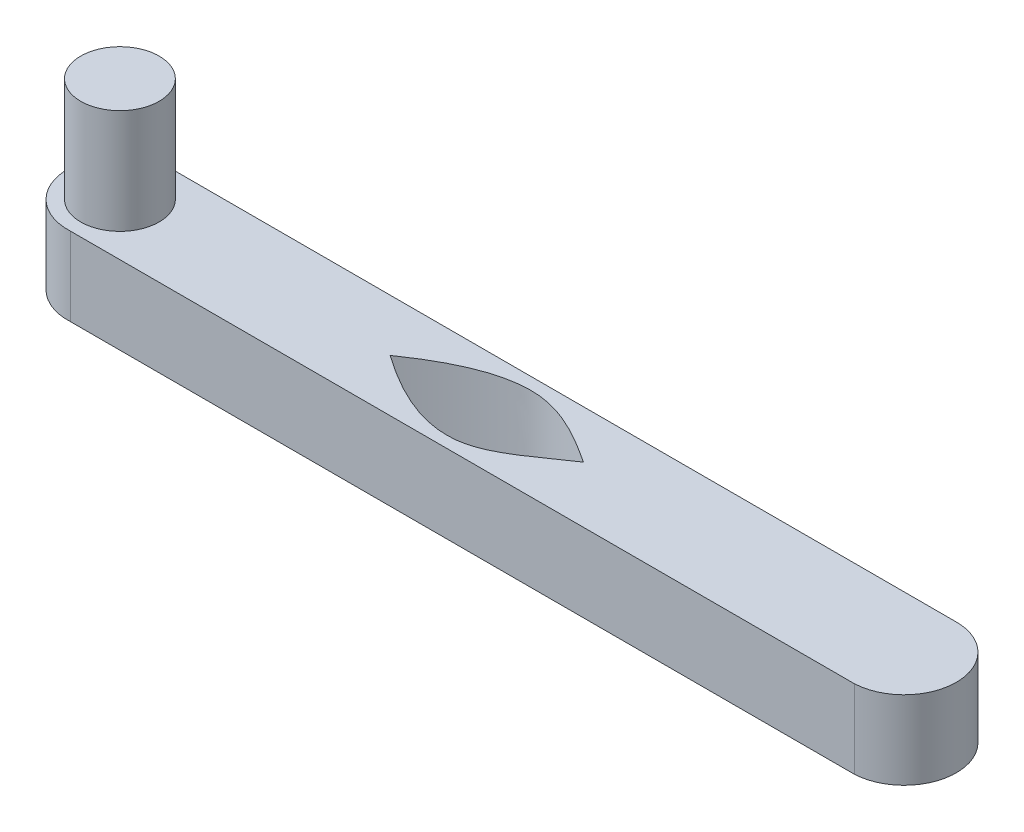
SolidWorks part; units mm, degrees
ref_plane "Alzado" through (0, 0, 0) normal (0, 0, 1) x (1, 0, 0)
ref_plane "Planta" through (0, 0, 0) normal (0, 1, 0) x (1, 0, 0)
ref_plane "Vista lateral" through (0, 0, 0) normal (1, 0, 0) x (0, 0, -1)
other "Centro de masa"
sketch "Croquis1" plane through (0, 0, 0) normal (0, 1, 0) x (1, 0, 0)
  line L0 (-61.9588, 0) -> (319.0412, 0)
  line L2 (-64.4776, 50.7365) -> (316.5224, 50.7365)
  arc A0 (-61.9588, 0) -> (-64.4776, 50.7365) centre (-63.2182, 25.3682) cw
  arc A1 (316.5224, 50.7365) -> (319.0412, 0) centre (317.7818, 25.3682) cw
  ellipse E0 centre (-63.2182, 25.3682) end of major axis (89.1818, 25.3682) minor radius 17.6626 (-63.4102, 7.7057) -> (-64.2865, 43.0304) ccw
  ellipse E1 centre (317.7818, 25.3682) end of major axis (470.1818, 25.3682) minor radius 17.6626 (316.9049, 43.0305) -> (318.6586, 7.706) ccw
  dimension "D3" = 152.4
  dimension "D1" = 381
  dimension "D2" = 381
  dimension "D4" = 152.4
extrude "Saliente-Extruir1" add sketch "Croquis1" along normal blind 38.1
sketch "Croquis2" plane through (0, 38.1, 0) normal (0, 1, 0) x (1, 0, 0)
  line L0 (-61.9588, 0) -> (319.0412, 0) construction
  line L1 (-64.4776, 50.7365) -> (316.5224, 50.7365) construction
  line L2 (-61.9588, 0) -> (319.0412, 0)
  line L3 (-64.4776, 50.7365) -> (316.5224, 50.7365)
  arc A0 (-64.4776, 50.7365) -> (-61.9588, 0) centre (-63.2182, 25.3682) ccw construction
  arc A1 (319.0412, 0) -> (316.5224, 50.7365) centre (317.7818, 25.3682) ccw construction
  arc A3 (319.0412, 0) -> (316.5224, 50.7365) centre (317.7818, 25.3682) ccw
  arc A4 (-64.4776, 50.7365) -> (-61.9588, 0) centre (-63.2182, 25.3682) ccw
sketch "Croquis3" plane through (0, 38.1, 0) normal (0, 1, 0) x (1, 0, 0)
  spline S0 degree 3 poles (0, 25.3682) (25.5964, 61.5196) (58.6773, 27.3727) (118.3628, -4.3558) (170.4737, 37.8015) (214.205, 57.3627) (239.3927, 25.3682) knots 0 0 0 0 0.293536 0.509769 0.658148 1 1 1 1
  spline S1 degree 3 poles (0, 25.3682) (25.3352, -11.2056) (59.2665, 24.3168) (147.3333, 68.3318) (200.0919, -25.9182) (239.3927, 25.3682) knots 0 0 0 0 0.293668 0.509999 1 1 1 1
extrude "Cortar-Extruir18" cut sketch "Croquis3" against normal blind 38.1 contours S1 S0
sketch "Croquis5" plane through (0, 38.1, 0) normal (0, 1, 0) x (1, 0, 0)
  circle A0 centre (-63.2182, 25.3682) radius 19.05
  dimension "D1" = 38.1
extrude "Saliente-Extruir2" add sketch "Croquis5" along normal blind 50.8
